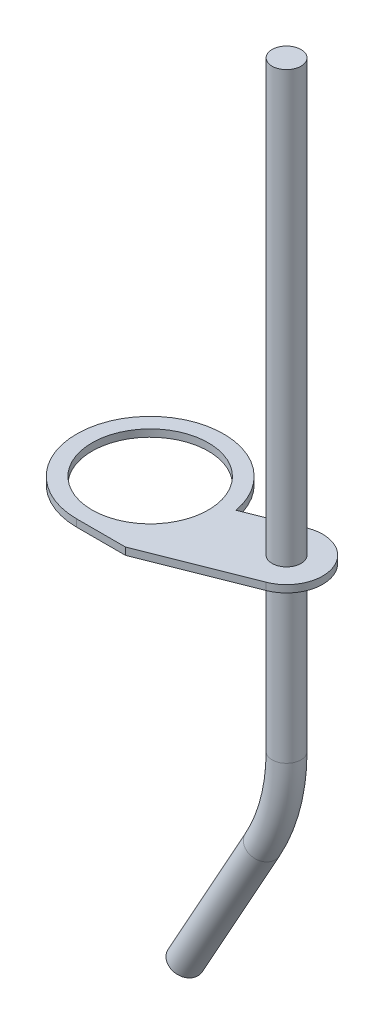
SolidWorks part; units mm, degrees
ref_plane "Front Plane" through (0, 0, 0) normal (0, 0, 1) x (1, 0, 0)
ref_plane "Top Plane" through (0, 0, 0) normal (0, 1, 0) x (1, 0, 0)
ref_plane "Right Plane" through (0, 0, 0) normal (1, 0, 0) x (0, 0, -1)
sketch "Sketch2" plane through (0, 0, 0) normal (0, 0, 1) x (1, 0, 0)
  line L0 (0, 0) -> (0, -83)
  line L1 (0, -55) -> (0, 55) construction
  line L2 (-3.3111, -95.7712) -> (-14, -115)
  arc A0 (0, -83) -> (-3.3111, -95.7712) centre (-26.2857, -83) cw
  point P5 (0, 0)
  point P9 (-4.5559, -99.3591)
  point P11 (10.5799, -65.0541)
  dimension "D1" = 115
  dimension "D2" = 14
  dimension "D3" = 83
  dimension "D4" = 22
sketch "Sketch4" plane through (0, 0, 0) normal (0, 1, 0) x (1, 0, 0)
  circle A0 centre (0, 0) radius 2
  dimension "D1" = 4
sweep "Sweep1" add profiles "Sketch4" path "Sketch2"
ref_plane "Plane1" through (0, -60, 0) normal (0, 1, 0) x (1, 0, 0)
sketch "Sketch5" plane through (0, -60, 0) normal (0, 1, 0) x (1, 0, 0)
  line L0 (-9.7614, 0) -> (9.7614, 0) construction
  line L1 (-18.84, -10.16) -> (-12.115, -10.16)
  line L2 (-12.115, -10.16) -> (1.8365, -4.6505)
  line L3 (-1.8365, 4.6505) -> (-8.8552, 1.8788)
  line L4 (-1.8365, 4.6505) -> (1.8365, -4.6505) construction
  arc A0 (-8.8552, 1.8788) -> (-18.84, -10.16) centre (-18.84, 0) ccw
  arc A1 (1.8365, -4.6505) -> (-1.8365, 4.6505) centre (0, 0) ccw
  point P12 (-14.7401, -10.16)
  point P13 (-8.5931, -10.16)
  point P14 (-8.5043, -10.16)
  dimension "D1" = 20.32
  dimension "D2" = 10
  dimension "D3" = 18.84
  dimension "D4" = 15
extrude "Boss-Extrude1" add sketch "Sketch5" along normal mid plane 1
sketch "Sketch6" plane through (0, -59.5, 0) normal (0, 1, 0) x (1, 0, 0)
  circle A0 centre (-18.84, 0) radius 8.04
  dimension "D1" = 16.08
extrude "Cut-Extrude1" cut sketch "Sketch6" against normal up to next
